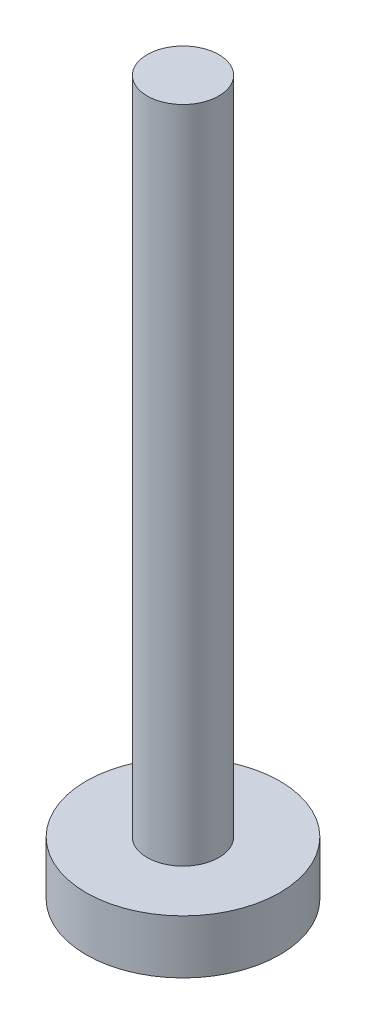
SolidWorks part; units mm, degrees
ref_plane "Front Plane" through (0, 0, 0) normal (0, 0, 1) x (1, 0, 0)
ref_plane "Top Plane" through (0, 0, 0) normal (0, 1, 0) x (1, 0, 0)
ref_plane "Right Plane" through (0, 0, 0) normal (1, 0, 0) x (0, 0, -1)
sketch "Sketch1" plane through (0, 0, 0) normal (0, 1, 0) x (1, 0, 0)
  circle A0 centre (0, 0) radius 6.858
  dimension "D1" = 13.716
extrude "Boss-Extrude1" add sketch "Sketch1" along normal blind 3.81
sketch "Sketch2" plane through (0, 3.81, 0) normal (0, 1, 0) x (1, 0, 0)
  circle A0 centre (0, 0) radius 2.54
  dimension "D1" = 5.08
extrude "Boss-Extrude2" add sketch "Sketch2" along normal blind 46.736
